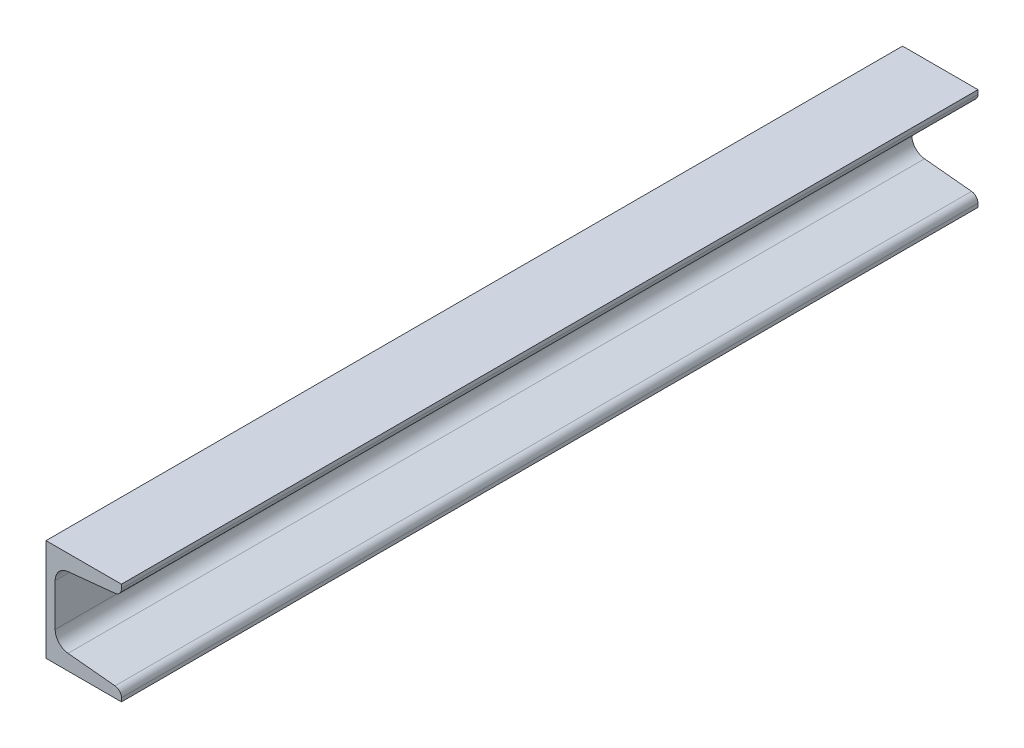
SolidWorks part; units mm, degrees
ref_plane "前视基准面" through (0, 0, 0) normal (0, 0, 1) x (1, 0, 0)
ref_plane "上视基准面" through (0, 0, 0) normal (0, 1, 0) x (1, 0, 0)
ref_plane "右视基准面" through (0, 0, 0) normal (1, 0, 0) x (0, 0, -1)
sketch "草图1" plane through (0, 0, 0) normal (0, 0, 1) x (1, 0, 0)
  line L0 (0, 0) -> (0, 50)
  line L1 (0, 0) -> (37, 0)
  line L2 (-55.9537, 25) -> (55.9537, 25) construction
  line L3 (0, 50) -> (37, 50)
  line L4 (4.5, 14.5099) -> (4.5, 35.2876)
  line L5 (16.25, -10) -> (16.25, 60) construction
  line L6 (10.8035, 7.5447) -> (33.8483, 5.2402)
  line L7 (37, 0) -> (37, 1.7575)
  line L8 (10.8035, 42.2529) -> (33.8483, 44.5574)
  line L9 (37, 48.04) -> (37, 50)
  arc A0 (10.8035, 42.2529) -> (4.5, 35.2876) centre (11.5, 35.2876) ccw
  arc A1 (4.5, 14.5099) -> (10.8035, 7.5447) centre (11.5, 14.5099) ccw
  arc A2 (33.8483, 44.5574) -> (37, 48.04) centre (33.5, 48.04) ccw
  arc A3 (37, 1.7575) -> (33.8483, 5.2402) centre (33.5, 1.7575) ccw
  point P7 (0, 25)
  point P11 (4.5, 25)
  point P14 (16.25, 25)
  point P15 (16.25, 7)
  point P17 (16.25, 43)
  point P19 (16.25, 43)
  point P20 (16.25, 7)
  point P23 (16.25, 43)
  dimension "D5" = 7
  dimension "D6" = 7
  dimension "D7" = 3.5
  dimension "D8" = 3.5
  dimension "h" = 50
  dimension "b" = 37
  dimension "d" = 4.5
  dimension "D1" = 16.25
  dimension "D2" = 7
  dimension "D3" = 5.711
  dimension "D4" = 5.711
extrude "凸台-拉伸1" add sketch "草图1" along normal blind 420
equation "\"高度\"= 50"
equation "\"腿宽\"= 37"
equation "\"腰宽\"= 4.5"
equation "\"h@草图1\"= \"高度\""
equation "\"d@草图1\"= \"腰宽\""
equation "\"D1@草图1\"= ( \"腿宽\" - \"腰宽\" ) / 2"
equation "\"平均腿厚\"= 7"
equation "\"内圆弧半径\"= 7"
equation "\"腿端圆弧半径\"= 3.5"
equation "\"D2@草图1\"= \"平均腿厚\""
equation "\"斜度\"= atn ( 0.1 )"
equation "\"D3@草图1\"= \"斜度\""
equation "\"D4@草图1\"= \"斜度\""
equation "\"D5@草图1\"= \"内圆弧半径\""
equation "\"D6@草图1\"= \"内圆弧半径\""
equation "\"D8@草图1\"= \"腿端圆弧半径\""
equation "\"D7@草图1\"= \"腿端圆弧半径\""
equation "\"b@草图1\"= \"腿宽\""
